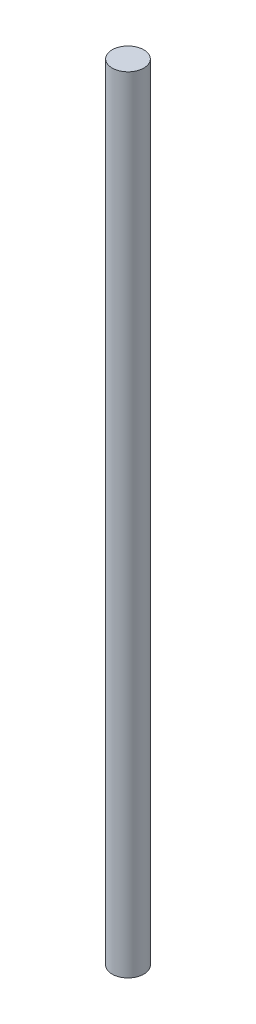
SolidWorks part; units mm, degrees
ref_plane "前视基准面" through (0, 0, 0) normal (0, 0, 1) x (1, 0, 0)
ref_plane "上视基准面" through (0, 0, 0) normal (0, 1, 0) x (1, 0, 0)
ref_plane "右视基准面" through (0, 0, 0) normal (1, 0, 0) x (0, 0, -1)
other "Configuration Table"
sketch "草图1" plane through (0, 0, 0) normal (0, 0, 1) x (1, 0, 0)
  line L0 (0, 67.5861) -> (0, -15.8613) construction
  line L2 (0, 0) -> (0, 40)
  line L6 (0, 40) -> (0, 44.8)
  line L7 (0, 44.8) -> (-1, 44.8)
  line L10 (0, 0) -> (0, -4.8)
  line L11 (0, -4.8) -> (-1, -4.8)
  line L14 (-1, 44.8) -> (-1, -4.8)
  dimension "D4" = 49.6
  dimension "D5" = 1
revolve "旋转1" add sketch "草图1" angle 360 about L0
